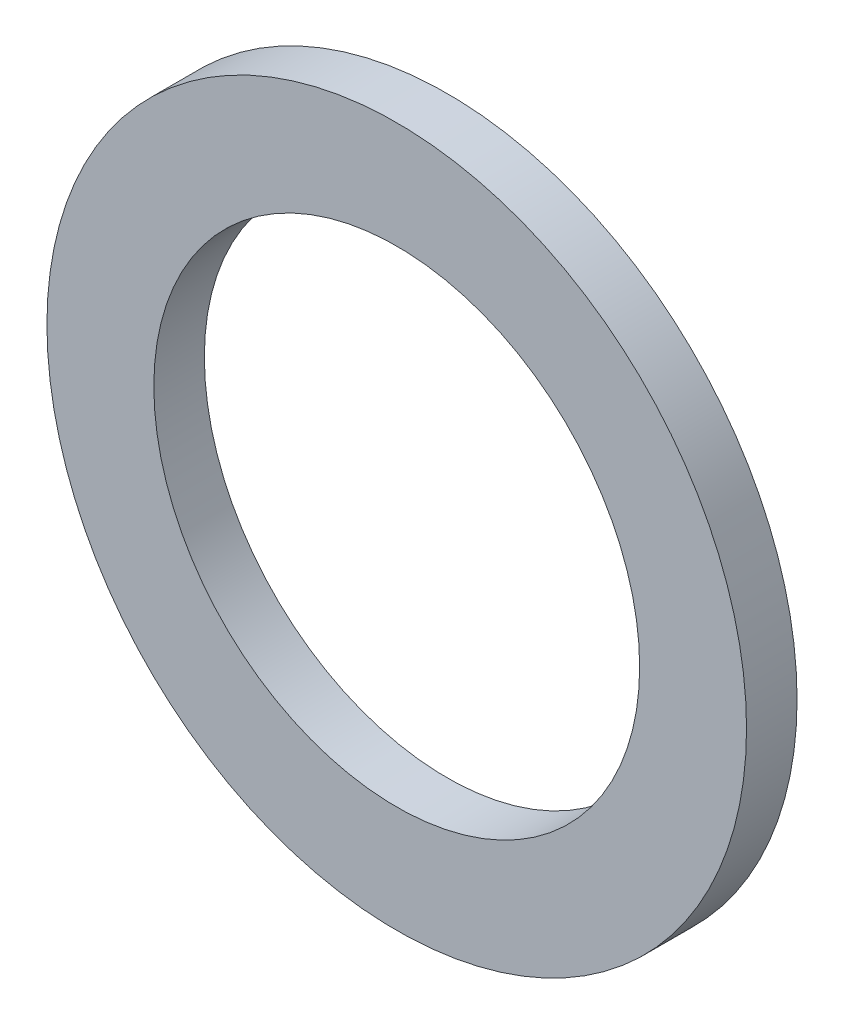
SolidWorks part; units mm, degrees
material "Латунь"
ref_plane "Спереди" through (0, 0, 0) normal (0, 0, 1) x (1, 0, 0)
ref_plane "Сверху" through (0, 0, 0) normal (0, 1, 0) x (1, 0, 0)
ref_plane "Справа" through (0, 0, 0) normal (1, 0, 0) x (0, 0, -1)
sketch "Эскиз1" plane through (0, 0, 0) normal (0, 0, 1) x (1, 0, 0)
  circle A0 centre (0, 0) radius 9
  circle A1 centre (0, 0) radius 6.25
extrude "Бобышка-Вытянуть1" add sketch "Эскиз1" along normal blind 1.3
